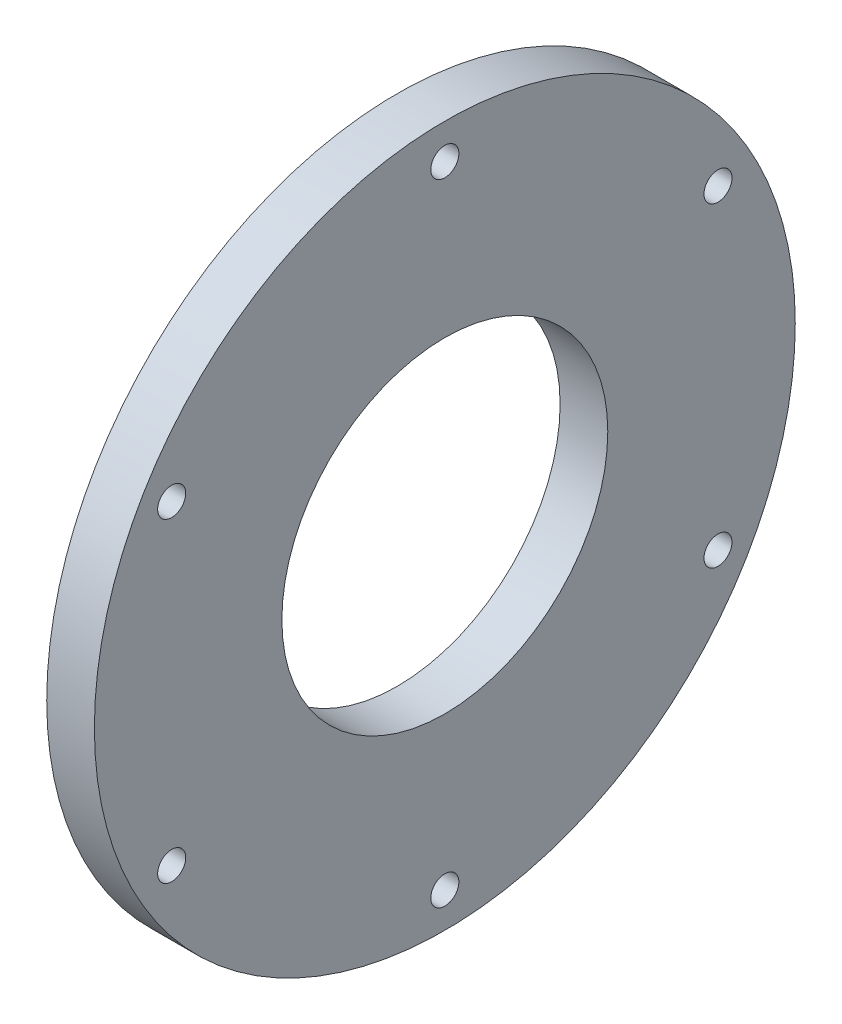
SolidWorks part; units mm, degrees
ref_plane "Front Plane" through (0, 0, 0) normal (0, 0, 1) x (1, 0, 0)
ref_plane "Top Plane" through (0, 0, 0) normal (0, 1, 0) x (1, 0, 0)
ref_plane "Right Plane" through (0, 0, 0) normal (1, 0, 0) x (0, 0, -1)
sketch "Sketch1" plane through (0, 0, 0) normal (1, 0, 0) x (0, 0, -1)
  circle A0 centre (0, 0) radius 100
  circle A1 centre (0, 0) radius 46.5
  dimension "D1" = 93
  dimension "D2" = 200
extrude "Boss-Extrude1" add sketch "Sketch1" along normal blind 13.6
sketch "Sketch2" plane through (0, 0, 0) normal (1, 0, 0) x (0, 0, -1)
  line L0 (0, 0) -> (-86.6025, 50) construction
  line L1 (0, 0) -> (0, 100) construction
  line L2 (0, 0) -> (-90, 0) construction
  line L3 (0, 0) -> (-77.9423, -45) construction
  circle A0 centre (0, 0) radius 90 construction
  circle A1 centre (0, 0) radius 100 construction
  point P3 (0, 90)
  point P5 (-77.9423, 45)
  point P12 (77.9423, 45)
  point P14 (-77.9423, -45)
  point P15 (0, -90)
  point P16 (77.9423, -45)
  dimension "D1" = 180
  dimension "D2" = 60
hole_wizard "Hole1" positions "Sketch3" profile "Sketch4" legacy
sketch "Sketch3" plane through (0, 0, 0) normal (-1, 0, 0) x (0, 0, 1)
  point P0 (-77.9423, 45)
  point P3 (0, 90)
  point P6 (77.9423, 45)
  point P12 (77.9423, -45)
  point P15 (0, -90)
  point P18 (-77.9423, -45)
  point P24 (0, 0)
  point P25 (0, 0)
sketch "Sketch4" plane through (0, 45, -77.9423) normal (0, 1, 0) x (0, 0, 1)
  line L0 (0, 0) -> (0, 17.4034)
  line L1 (0, 17.4034) -> (4, 15)
  line L2 (4, 15) -> (4, 2)
  line L3 (4, 2) -> (7.5, 2)
  line L4 (7.5, 2) -> (7.5, 0)
  line L5 (7.5, 0) -> (0, 0)
  line L10 (0, 17.4034) -> (-4, 15) construction
  line L11 (0, -6.35) -> (0, 107.95) construction
  dimension "Hole Dia." = 8
  dimension "Hole Depth" = 15
  dimension "C'Bore Dia." = 15
  dimension "C'Bore Depth" = 2
  dimension "Drill Angle" = 118
